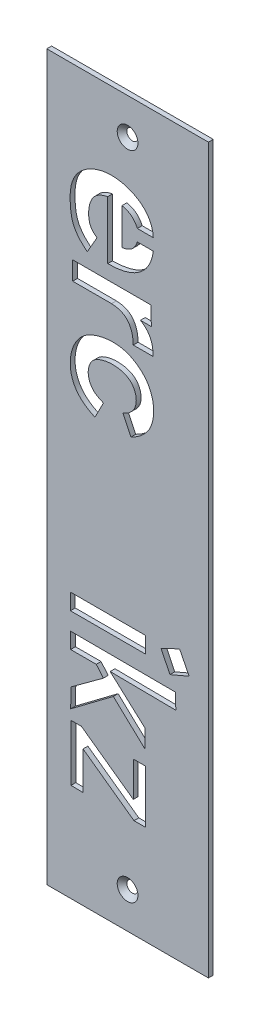
SolidWorks part; units mm, degrees
ref_plane "Ebene vorne" through (0, 0, 0) normal (0, 0, 1) x (1, 0, 0)
ref_plane "Ebene oben" through (0, 0, 0) normal (0, 1, 0) x (1, 0, 0)
ref_plane "Ebene rechts" through (0, 0, 0) normal (1, 0, 0) x (0, 0, -1)
sketch "Skizze2" plane through (0, 0, 0) normal (0, 0, 1) x (1, 0, 0)
  line L0 (-3.0455, 96.1466) -> (63.9545, 96.1466)
  line L1 (63.9545, 96.1466) -> (63.9545, -203.8534)
  line L2 (63.9545, -203.8534) -> (-3.0455, -203.8534)
  line L3 (-3.0455, -203.8534) -> (-3.0455, 96.1466)
  point P3 (-3.0455, 96.1466)
  dimension "D1" = 67
  dimension "D2" = 300
extrude "Aufsatz-Linear austragen1" add sketch "Skizze2" along normal blind 2
hole_wizard "Formsenkung für M4 Senkschraube mit Innensechskant1" positions "Skizze3" profile "Skizze4" countersink size "M4" standard "DIN" end condition through all
sketch "Skizze3" plane through (0, 0, 2) normal (0, 0, 1) x (1, 0, 0)
  line L0 (30.4545, 96.1466) -> (30.4545, -203.8534) construction
  line L1 (63.9545, 96.1466) -> (-3.0455, 96.1466) construction
  line L2 (-3.0455, -203.8534) -> (63.9545, -203.8534) construction
  point P11 (30.4545, -188.8534)
  point P13 (30.4545, 81.1466)
  dimension "D1" = 15
  dimension "D2" = 15
sketch "Skizze4" plane through (30.4545, 81.1466, 2) normal (1, 0, 0) x (0, -1, 0)
  line L0 (0, 0) -> (0, 2)
  line L1 (0, 2) -> (2.25, 2)
  line L2 (2.25, 2) -> (2.25, 2.05)
  line L3 (2.25, 2.05) -> (4.3, 0)
  line L5 (4.3, 0) -> (0, 0)
  line L6 (-2.25, 2.05) -> (-4.3, 0) construction
  line L11 (0, -6.35) -> (0, 107.95) construction
  dimension "Bohrerdurchmesser" = 4.5
  dimension "Bohrungstiefe" = 2
  dimension "Senkdurchmesser (Oben)" = 8.6
  dimension "Senkwinkel (Oben)" = 90
sketch "Skizze9" plane through (0, 0, 2) normal (0, 0, 1) x (1, 0, 0)
  line L0 (277.3103, -91.1322) -> (277.3103, -741.7989) construction
  line L1 (162.6667, 274.5) -> (813.3333, 274.5) construction
  line L2 (278.0335, -92.9422) -> (278.0335, -743.6089) construction
  line L3 (25.4545, 83.4466) -> (25.4545, -188.8534) construction
  line L4 (279.8115, -242.9411) -> (279.8115, -893.6078) construction
  line L5 (52.0016, -91.6923) -> (55.9549, -99.5308)
  line L6 (6.7588, -93.9334) -> (37.8638, -93.9334)
  line L7 (6.7588, -93.9334) -> (6.7588, -100.644)
  line L8 (6.7588, -100.644) -> (37.8638, -100.644)
  line L9 (37.8638, -93.9334) -> (37.8638, -100.644)
  line L10 (52.0016, -91.6923) -> (44.3317, -95.4136)
  line L11 (55.9549, -99.5308) -> (48.0172, -102.9409)
  line L12 (44.3317, -95.4136) -> (48.0172, -102.9409)
  line L13 (6.7588, -107.9259) -> (50.3504, -108.0881)
  line L14 (50.3504, -108.0881) -> (50.4277, -114.5082)
  line L15 (50.4277, -114.5082) -> (23.2172, -114.2143)
  line L16 (23.2172, -114.2143) -> (37.7586, -127.3748)
  line L17 (37.7586, -127.3748) -> (37.7586, -134.9208)
  line L18 (37.7586, -134.9208) -> (24.5331, -122.513)
  line L19 (24.5331, -122.513) -> (6.8761, -135.7927)
  line L20 (6.8761, -135.7927) -> (6.9863, -127.8673)
  line L21 (6.9863, -127.8673) -> (20.3982, -118.0338)
  line L22 (20.3982, -118.0338) -> (17.4744, -114.5082)
  line L23 (17.4744, -114.5082) -> (6.8414, -114.5082)
  line L24 (6.8414, -114.5082) -> (6.7588, -107.9259)
  line L25 (32.8138, -140.8338) -> (37.9561, -140.8338)
  line L26 (37.9561, -140.8338) -> (37.8638, -162.8087)
  line L27 (37.8638, -162.8087) -> (33.1043, -162.8087)
  line L28 (33.1043, -162.8087) -> (12.0075, -147.6113)
  line L29 (12.0075, -147.6113) -> (12.0075, -163.2877)
  line L30 (12.0075, -163.2877) -> (6.9863, -163.2037)
  line L31 (6.9863, -163.2037) -> (6.9863, -139.8453)
  line L32 (6.9863, -139.8453) -> (11.3229, -139.8453)
  line L33 (11.3229, -139.8453) -> (32.8138, -155.3266)
  line L34 (32.8138, -155.3266) -> (32.8138, -140.8338)
  line L35 (7.6897, 25.7878) -> (7.6897, 18.1068)
  line L36 (7.6897, 18.1068) -> (23.7949, 18.1068)
  line L37 (7.6897, 25.7878) -> (40.0916, 25.7878)
  line L38 (40.0916, 25.7878) -> (40.31, 18.1068)
  line L39 (40.31, 18.1068) -> (35.7698, 18.1068)
  line L40 (32.8013, 7.7502) -> (41.0129, 7.7502)
  line L41 (28.4889, -18.7703) -> (31.8174, -25.7897)
  line L42 (20.4315, -19.2453) -> (16.9237, -26.0653)
  line L43 (22.1826, 55.6835) -> (22.1826, 31.6463)
  line L44 (28.1201, 55.4466) -> (28.1201, 40.4402)
  line L45 (34.5038, 45.5913) -> (41.105, 45.5913)
  line L46 (34.5038, 50.4224) -> (41.1043, 50.4224)
  line L47 (17.8145, 38.7682) -> (13.7593, 31.7561)
  line L48 (6.7381, 44.7029) -> (6.7381, -215.8156) construction
  line L49 (40.0916, 25.7878) -> (40.0916, -185.0114) construction
  spline S0 degree 2 poles (23.7949, 18.1068) (32.6012, 17.824) (32.8013, 7.7502) knots 0 0 0 1 1 1
  spline S1 degree 2 poles (35.7698, 18.1068) (41.2162, 15.0598) (41.0129, 7.7502) knots 0 0 0 1 1 1
  spline S2 degree 3 poles (20.4315, -19.2453) (18.53, -18.4488) (16.6195, -17.4252) (13.8133, -13.5116) (14.1212, -6.4839) (18.3101, -4.4186) (22.6732, -3.4854) (24.799, -3.4186) (28.7374, -3.9608) (33.2318, -6.0118) (34.587, -11.5698) (32.7477, -16.3445) (30.562, -18.0532) (28.4889, -18.7703) knots 0 0 0 0 0.057281 0.077975 0.20694 0.412118 0.446671 0.540715 0.566135 0.689115 0.842005 0.873093 1 1 1 1
  spline S3 degree 3 poles (31.8174, -25.7897) (35.4982, -24.0191) (42.4053, -18.0742) (41.2137, -2.0095) (30.919, 4.1413) (22.7762, 4.8314) (17.5729, 3.892) (9.4417, -0.4133) (6.136, -7.9214) (7.3223, -18.8881) (11.205, -23.6735) (16.9237, -26.0653) knots 0 0 0 0 0.11941 0.279254 0.419931 0.450284 0.568056 0.605463 0.78694 0.828662 1 1 1 1
  spline S4 degree 2 poles (28.1201, 40.4402) (33.0163, 40.8999) (34.5038, 45.5913) knots 0 0 0 1 1 1
  spline S5 degree 2 poles (28.1201, 55.4466) (32.6501, 54.6081) (34.5038, 50.4224) knots 0 0 0 1 1 1
  spline S6 degree 3 poles (22.1826, 31.6463) (28.2852, 31.6882) (36.4935, 34.093) (40.5505, 41.1674) (41.105, 45.5913) knots 0 0 0 0 0.55539 1 1 1 1
  spline S7 degree 3 poles (17.8145, 38.7682) (15.599, 40.1458) (13.9175, 43.7823) (14.5336, 51.2952) (17.8929, 54.8196) (22.1826, 55.6835) knots 0 0 0 0 0.220877 0.573734 1 1 1 1
  spline S8 degree 3 poles (13.7593, 31.7561) (12.0699, 33.0078) (8.027, 37.0033) (6.5231, 43.013) (6.6283, 56.3113) (15.2614, 63.4982) (30.1206, 65.2154) (40.7745, 58.5238) (41.1043, 50.4224) knots 0 0 0 0 0.090008 0.234551 0.339423 0.540898 0.687756 1 1 1 1
  point P17 (55.3504, -108.0881)
  point P22 (55.4277, -114.5082)
  point P23 (28.2172, -114.2143)
  point P24 (42.7586, -127.3748)
  point P25 (42.7586, -134.9208)
  point P26 (29.5331, -122.513)
  point P27 (11.8761, -135.7927)
  point P28 (11.9863, -127.8673)
  point P29 (25.3982, -118.0338)
  point P30 (22.4744, -114.5082)
  point P31 (11.8414, -114.5082)
  point P32 (11.7588, -107.9259)
extrude "Schnitt-Linear austragen5" cut sketch "Skizze9" against normal blind 10
